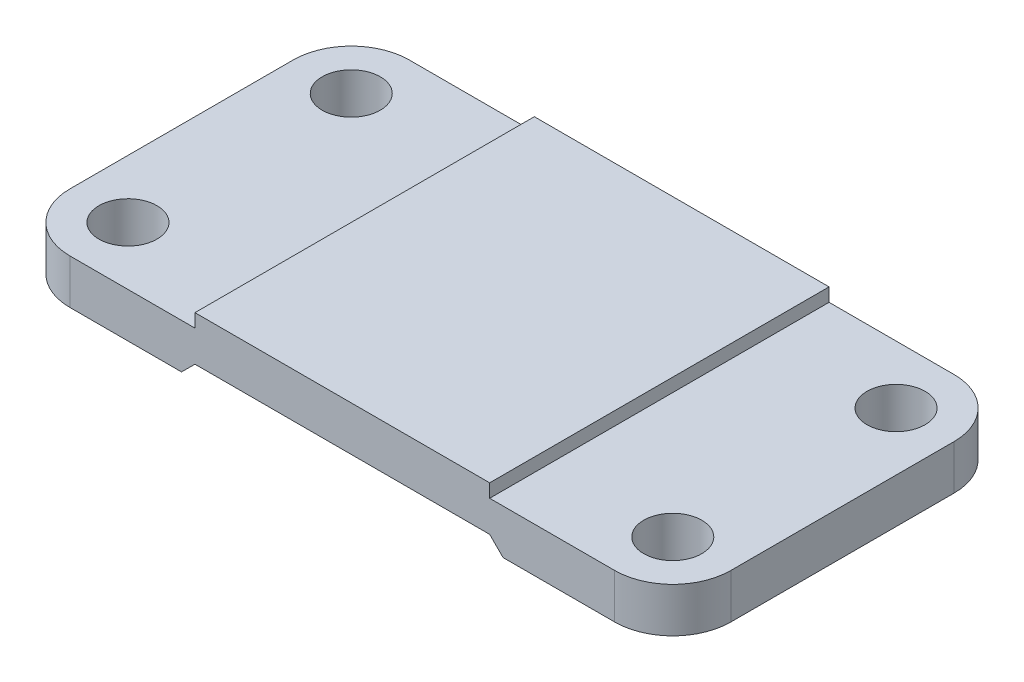
SolidWorks part; units mm, degrees
ref_plane "Front Plane" through (0, 0, 0) normal (0, 0, 1) x (1, 0, 0)
ref_plane "Top Plane" through (0, 0, 0) normal (0, 1, 0) x (1, 0, 0)
ref_plane "Right Plane" through (0, 0, 0) normal (1, 0, 0) x (0, 0, -1)
sketch "Sketch1" plane through (0, 0, 0) normal (0, 1, 0) x (1, 0, 0)
  line L12 (0, 38) -> (0, -38) construction
  line L13 (-61, 38) -> (61, 38)
  line L14 (-74, 25) -> (-74, -25)
  line L15 (-61, -38) -> (61, -38)
  line L16 (74, 25) -> (74, -25)
  line L17 (-74, 38) -> (74, -38) construction
  line L18 (-74, -38) -> (74, 38) construction
  line L19 (-74, 0) -> (74, 0) construction
  arc A0 (-74, -25) -> (-61, -38) centre (-61, -25) ccw
  arc A1 (61, -38) -> (74, -25) centre (61, -25) ccw
  arc A2 (61, 38) -> (74, 25) centre (61, 25) cw
  arc A3 (-61, 38) -> (-74, 25) centre (-61, 25) ccw
  circle A4 centre (-61, 25) radius 6.5
  circle A5 centre (61, 25) radius 6.5
  circle A6 centre (61, -25) radius 6.5
  circle A7 centre (-61, -25) radius 6.5
  point P0 (0, 0)
  dimension "D3" = 13
  dimension "D4" = 13
  dimension "D1" = 148
  dimension "D2" = 76
extrude "Boss-Extrude1" add sketch "Sketch1" against normal blind 10
sketch "Sketch2" plane through (0, 0, 38) normal (0, 0, 1) x (1, 0, 0)
  line L0 (-36, -10) -> (36, -10)
  line L1 (-61, -10) -> (61, -10) construction
  line L2 (36, -10) -> (33, -7)
  line L3 (33, -7) -> (-33, -7)
  line L4 (-33, -7) -> (-36, -10)
  line L5 (-33, 0) -> (-33, 2.925)
  line L6 (-61, 0) -> (61, 0) construction
  point P4 (0, -7)
  point P7 (0, -10)
  dimension "D1" = 72
  dimension "D2" = 45
  dimension "D3" = 3
extrude "Cut-Extrude1" cut sketch "Sketch2" against normal through all contours L0 L2 L3 L4
sketch "Sketch3" plane through (0, 0, 38) normal (0, 0, 1) x (1, 0, 0)
  line L0 (-33, 0) -> (-33, 3)
  line L1 (-61, 0) -> (61, 0) construction
  line L2 (-33, 3) -> (33, 3)
  line L3 (33, 3) -> (33, 0)
  line L4 (33, 0) -> (-33, 0)
  point P4 (0, 3)
  dimension "D1" = 3
  dimension "D2" = 66
extrude "Boss-Extrude2" add sketch "Sketch3" against normal through all
